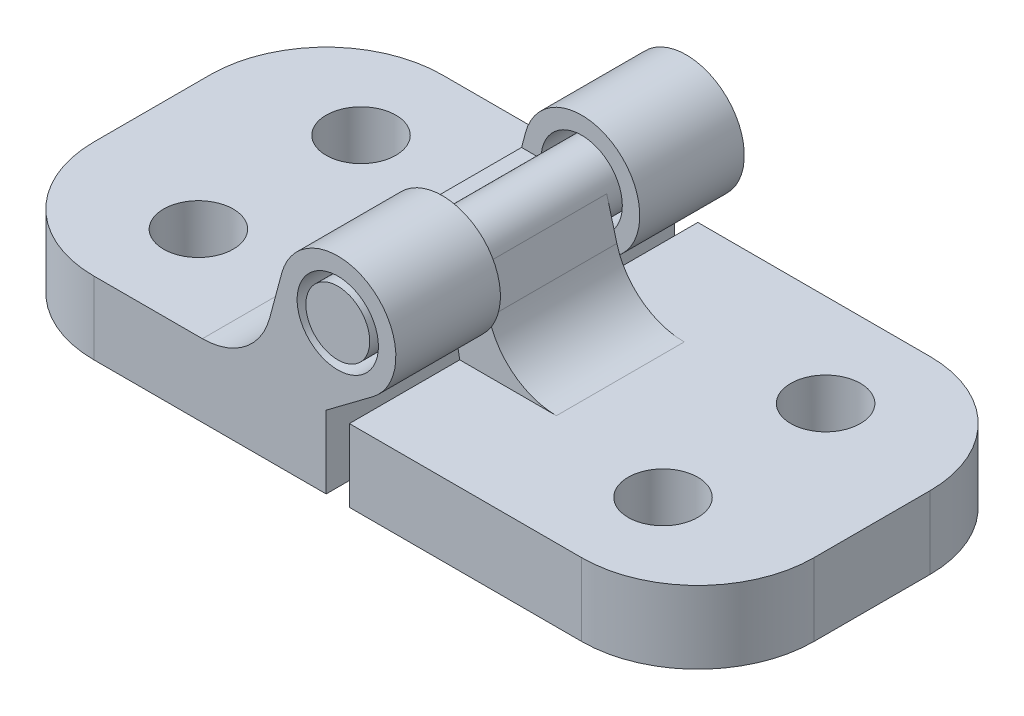
SolidWorks part; units mm, degrees
ref_plane "Front Plane" through (0, 0, 0) normal (0, 0, 1) x (1, 0, 0)
ref_plane "Top Plane" through (0, 0, 0) normal (0, 1, 0) x (1, 0, 0)
ref_plane "Right Plane" through (0, 0, 0) normal (1, 0, 0) x (0, 0, -1)
sketch "Sketch2" plane through (0, 0, 0) normal (0, 1, 0) x (1, 0, 0)
  line L0 (0, -55) -> (0, 55) construction
  line L5 (-55, 0) -> (55, 0) construction
  line L6 (-15.5, -7.5) -> (-0.5, -7.5)
  line L7 (-15.5, -7.5) -> (-15.5, 7.5)
  line L12 (-15.5, 7.5) -> (-0.5, 7.5)
  line L13 (-0.5, -7.5) -> (-0.5, 7.5)
  line L14 (-15.5, -7.5) -> (-0.5, 7.5) construction
  line L15 (-15.5, 7.5) -> (-0.5, -7.5) construction
  line L17 (15.5, 7.5) -> (0.5, -7.5) construction
  line L18 (15.5, -7.5) -> (0.5, 7.5) construction
  line L19 (0.5, -7.5) -> (0.5, 7.5)
  line L20 (15.5, 7.5) -> (0.5, 7.5)
  line L21 (15.5, -7.5) -> (15.5, 7.5)
  line L22 (15.5, -7.5) -> (0.5, -7.5)
  point P0 (-8, 0)
  point P7 (0, 0)
  point P14 (8, 0)
  dimension "D1" = 15
  dimension "D2" = 15
  dimension "D3" = 8
extrude "Boss-Extrude1" add sketch "Sketch2" along normal blind 3.125 contours L7 L12 L13 L6 | L22 L19 L20 L21
sketch "Sketch3" plane through (0, 0, 7.5) normal (0, 0, 1) x (1, 0, 0)
  line L0 (-15.5, 3.125) -> (-0.5, 3.125) construction
  line L1 (-0.5, 3.125) -> (1.5, 4.625)
  line L2 (-2.4148, 7.272) -> (-3.526, 3.125)
  line L3 (-3.526, 3.125) -> (-0.5, 3.125)
  line L4 (-0.5, 3.125) -> (-0.5, 0) construction
  arc A0 (1.5, 4.625) -> (-2.4148, 7.272) centre (0, 6.625) ccw
  circle A1 centre (0, 6.625) radius 1.75
  point P11 (-3.4631, 3.125)
  dimension "D1" = 5
  dimension "D3" = 3.5
  dimension "D2" = 3.5
  dimension "D4" = 0.5
  dimension "D5" = 75
extrude "Boss-Extrude2" add sketch "Sketch3" against normal up to surface (15 mm away) up to face at (-8, 1.5625, -7.5)
sketch "Sketch4" plane through (0, 0, 0) normal (1, 0, 0) x (0, 0, -1)
  line L1 (-3, 3.375) -> (3, 3.375)
  line L2 (-3, 3.375) -> (-3, 9.125)
  line L3 (-3, 9.125) -> (3, 9.125)
  line L4 (3, 3.375) -> (3, 9.125)
  line L5 (-3, 3.375) -> (3, 9.125) construction
  line L6 (-3, 9.125) -> (3, 3.375) construction
  line L8 (7.5, 9.125) -> (-7.5, 9.125) construction
  line L9 (0, 5.0187) -> (0, -5.0187) construction
  line L11 (-7.5, 3.125) -> (7.5, 3.125) construction
  point P0 (0, 6.25)
  dimension "D2" = 6
  dimension "D3" = 3
  dimension "D1" = 0.25
extrude "Cut-Extrude1" cut sketch "Sketch4" along normal up to next
sketch "Sketch9" plane through (0, 0, 0) normal (1, 0, 0) x (0, 0, -1)
  line L1 (-3, 9.125) -> (3, 9.125)
  line L2 (-3, 9.125) -> (-3, 6.625)
  line L3 (-3, 6.625) -> (3, 6.625)
  line L4 (3, 9.125) -> (3, 6.625)
  line L5 (3, 9.125) -> (-3, 9.125) construction
  line L6 (-3, 9.125) -> (-3, 8.375) construction
  line L8 (3, 8.375) -> (3, 9.125) construction
  dimension "D1" = 2.5
extrude "Cut-Extrude4" cut sketch "Sketch9" against normal up to next
sketch "Sketch5" plane through (0, 0, 0) normal (0, 0, 1) x (1, 0, 0)
  line L0 (0.1243, 5.2556) -> (0.5, 3.125)
  line L1 (0.5, 3.125) -> (2.3613, 3.125)
  line L2 (2.3613, 3.125) -> (1.3281, 6.9809)
  line L3 (15.5, 3.125) -> (0.5, 3.125) construction
  arc A0 (1.3281, 6.9809) -> (0.1243, 5.2556) centre (0, 6.625) ccw
  circle A1 centre (0, 6.625) radius 1.75 construction
  point P1 (2.6407, 3.125)
  point P10 (0, 0)
  point P11 (0.3306, 3.125)
  point P12 (0, 0)
  point P13 (0.7041, 3.125)
  point P14 (0, 0)
  point P15 (0, 0)
  point P16 (0, 5.6291)
  point P17 (0, 0)
  point P19 (0.3918, 5.205)
  dimension "D1" = 2.75
  dimension "D2" = 100
  dimension "D3" = 75
extrude "Boss-Extrude3" add sketch "Sketch5" along normal offset from surface 0.25 and the other way offset from surface (2.75 mm away) 0.25 up to face at (-0.2138, 6.397, 3) other way up to face at (-0.2138, 6.397, -3)
sketch "Sketch7" plane through (0, 0, 0) normal (0, 0, 1) x (1, 0, 0)
  circle A0 centre (0, 6.625) radius 1.375
  arc A2 (1.3281, 6.9809) -> (0.1243, 5.2556) centre (0, 6.625) ccw construction
extrude "Boss-Extrude4" add sketch "Sketch7" along normal up to surface and the other way up to surface
sketch "Sketch8" plane through (0, 3.125, 0) normal (0, 1, 0) x (1, 0, 0)
  line L0 (-5.0187, 0) -> (5.0187, 0) construction
  line L1 (0, -5.0187) -> (0, 5.0187) construction
  circle A0 centre (-10, 3.5) radius 1.5
  circle A1 centre (-10, -3.5) radius 1.5
  circle A2 centre (10, -3.5) radius 1.5
  circle A3 centre (10, 3.5) radius 1.5
  dimension "D1" = 3
  dimension "D2" = 3.5
  dimension "D3" = 10
extrude "Cut-Extrude2" cut sketch "Sketch8" against normal up to next (3.125 mm away)
fillet "Fillet1" radius 5 2 edges at (-15.5, 1.5625, -7.5) (-15.5, 1.5625, 7.5)
fillet "Fillet2" radius 5 2 edges at (15.5, 1.5625, 7.5) (15.5, 1.5625, -7.5)
fillet "Fillet3" radius 3 1 edges at (-3.526, 3.125, 0)
fillet "Fillet4" radius 3 1 edges at (2.3613, 3.125, 0)
equation "\"D3@Sketch2\"=\"D2@Sketch2\"/2+.5"
equation "\"D2@Sketch3\"=\"D1@Sketch3\"/2+1"
equation "\"D3@Sketch4\"=\"D2@Sketch4\"/2"
